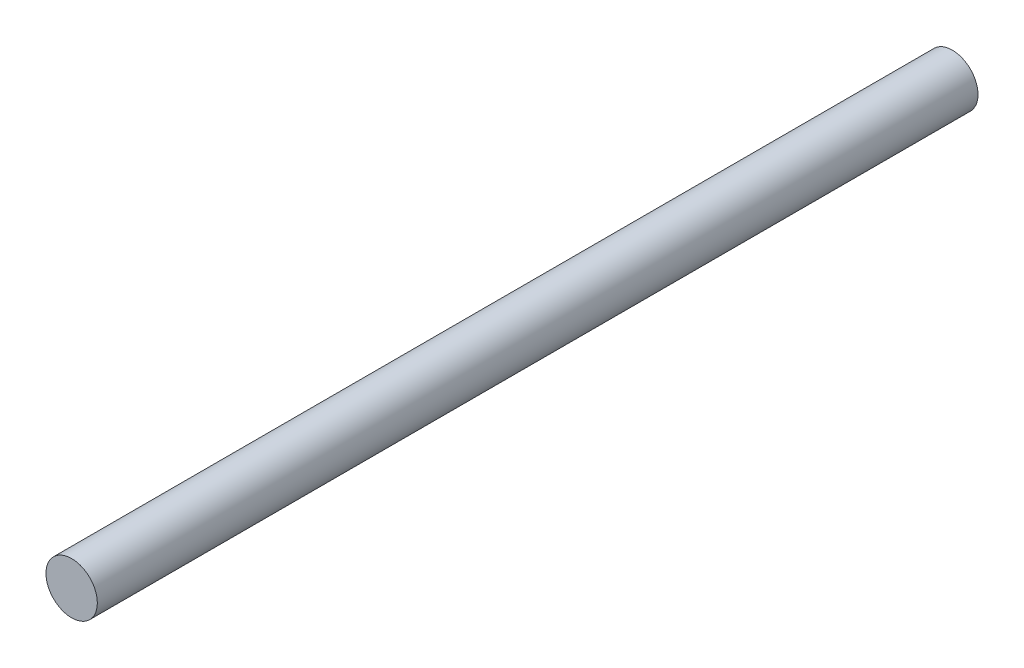
SolidWorks part; units mm, degrees
material "Alumina"
ref_plane "Front Plane" through (0, 0, 0) normal (0, 0, 1) x (1, 0, 0)
ref_plane "Top Plane" through (0, 0, 0) normal (0, 1, 0) x (1, 0, 0)
ref_plane "Right Plane" through (0, 0, 0) normal (1, 0, 0) x (0, 0, -1)
sketch "Sketch1" plane through (0, 0, 0) normal (0, 0, 1) x (1, 0, 0)
  circle A0 centre (0, 0) radius 7
  dimension "D1" = 14
extrude "Boss-Extrude1" add sketch "Sketch1" along normal blind 240
equation "\"shaftDiameter\"= 14mm"
equation "\"shaftLength\"= 240mm"
equation "\"D1@Sketch1\"=\"shaftDiameter\""
equation "\"D1@Boss-Extrude1\"=\"shaftLength\""
